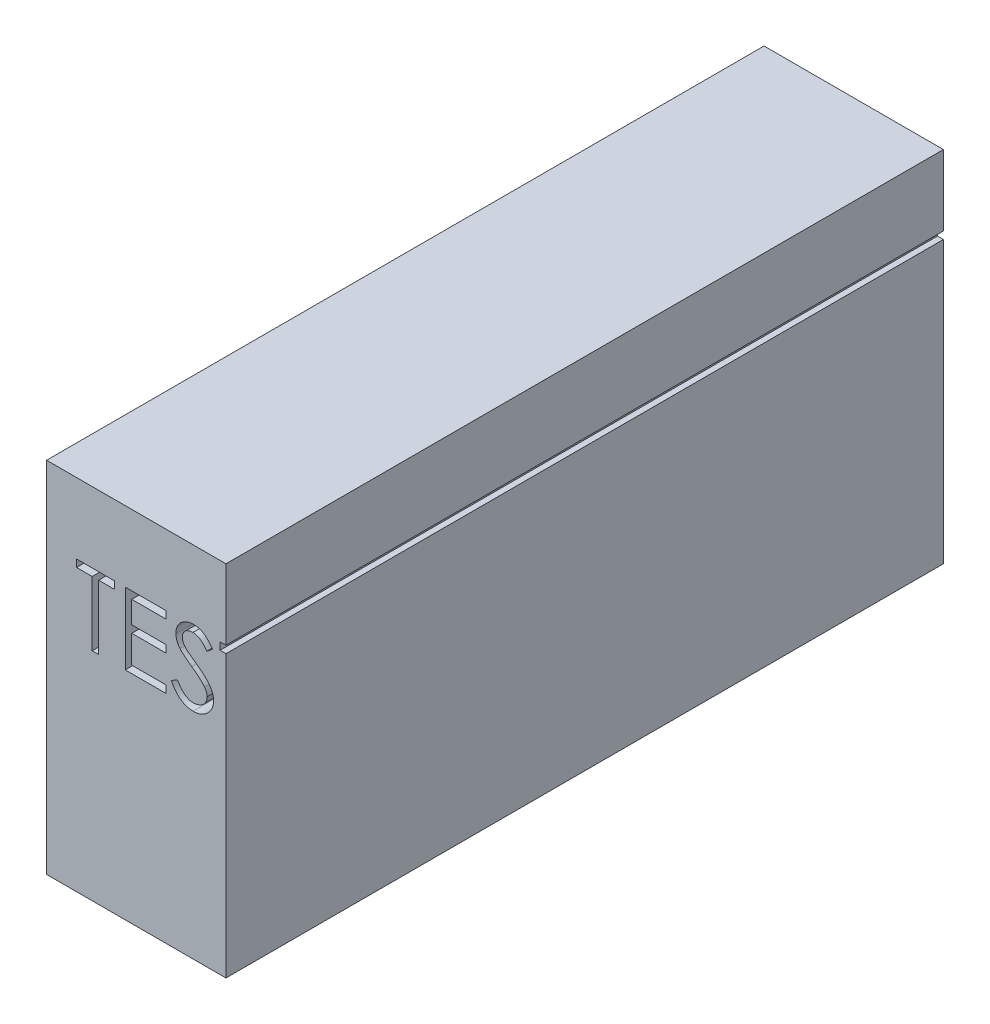
SolidWorks part; units mm, degrees
ref_plane "Front Plane" through (0, 0, 0) normal (0, 0, 1) x (1, 0, 0)
ref_plane "Top Plane" through (0, 0, 0) normal (0, 1, 0) x (1, 0, 0)
ref_plane "Right Plane" through (0, 0, 0) normal (1, 0, 0) x (0, 0, -1)
sketch "Sketch1" plane through (0, 0, 0) normal (0, 0, 1) x (1, 0, 0)
  line L1 (-25, 50) -> (25, 50)
  line L2 (-25, 50) -> (-25, -50)
  line L3 (-25, -50) -> (25, -50)
  line L4 (25, 50) -> (25, -50)
  line L5 (-25, 50) -> (25, -50) construction
  line L6 (-25, -50) -> (25, 50) construction
  point P0 (0, 0)
  dimension "D1" = 100
  dimension "D2" = 50
extrude "Extrude1" add sketch "Sketch1" along normal blind 200
sketch "Sketch2" plane through (0, 0, 200) normal (0, 0, 1) x (1, 0, 0)
  text T0 "TEST" font "Century Gothic" height 20
extrude "Extrude2" cut sketch "Sketch2" against normal blind 300
